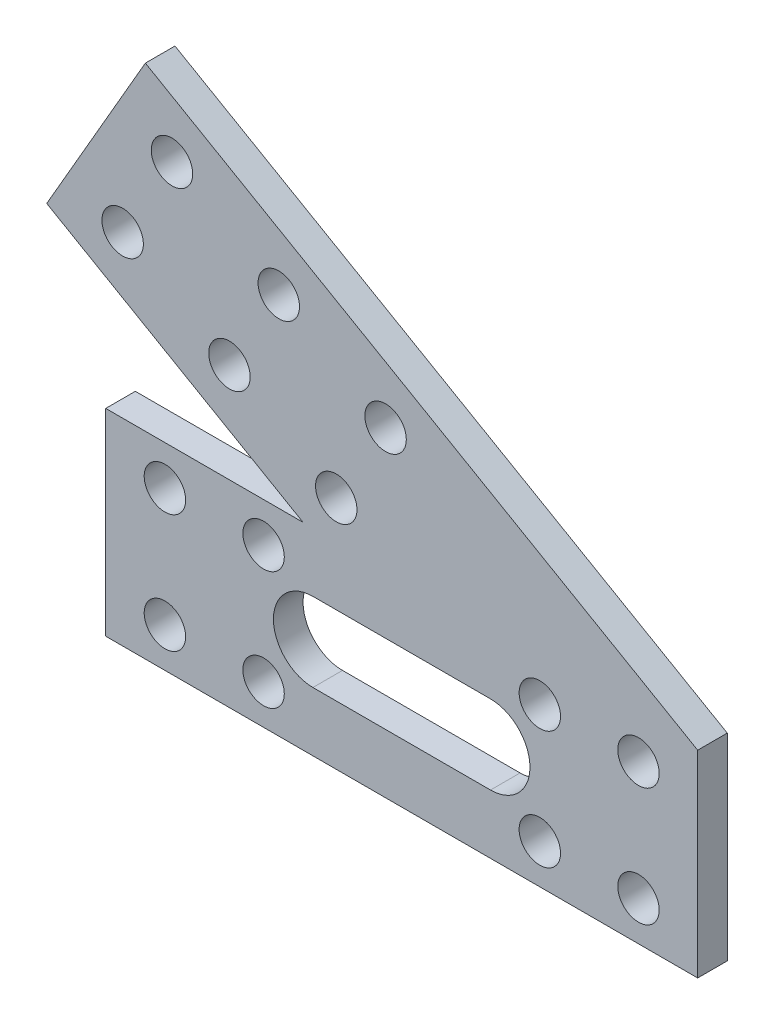
SolidWorks part; units mm, degrees
material "Thornel VCB-20 碳布"
ref_plane "前视基准面" through (0, 0, 0) normal (0, 0, 1) x (1, 0, 0)
ref_plane "上视基准面" through (0, 0, 0) normal (0, 1, 0) x (1, 0, 0)
ref_plane "右视基准面" through (0, 0, 0) normal (1, 0, 0) x (0, 0, -1)
other "Configuration Table"
sketch "草图1" plane through (0, 0, 0) normal (0, 0, 1) x (1, 0, 0)
  line L0 (60, 0) -> (0, 0)
  line L1 (0, 0) -> (0, 20)
  line L2 (0, 20) -> (60, 20) construction
  line L9 (60, 20) -> (60, 0)
  line L11 (20, 20) -> (-5.9808, 35)
  line L12 (-5.9808, 35) -> (4.0192, 52.3205)
  line L13 (4.0192, 52.3205) -> (60, 20)
  line L14 (20, 20) -> (0, 20)
  dimension "D1" = 20
  dimension "D2" = 60
  dimension "D3" = 150
  dimension "D4" = 30
  dimension "D5" = 20
  dimension "D6" = 30
extrude "凸台-拉伸1" add sketch "草图1" along normal blind 3
sketch "草图2" plane through (0, 0, 3) normal (0, 0, 1) x (1, 0, 0)
  line L0 (6.7154, 44.9904) -> (1.7154, 36.3301) construction
  line L1 (1.7154, 36.3301) -> (23.366, 23.8301) construction
  line L2 (23.366, 23.8301) -> (28.366, 32.4904) construction
  line L3 (28.366, 32.4904) -> (6.7154, 44.9904) construction
  line L4 (4.0192, 52.3205) -> (-5.9808, 35) construction
  line L5 (-5.9808, 35) -> (20, 20) construction
  line L6 (60, 20) -> (4.0192, 52.3205) construction
  line L7 (12.5407, 30.0801) -> (17.5407, 38.7404) construction
  line L9 (20, 20) -> (0, 20) construction
  line L10 (6, 16) -> (54, 16) construction
  line L11 (6, 16) -> (6, 4) construction
  line L12 (6, 4) -> (54, 4) construction
  line L13 (54, 16) -> (54, 4) construction
  line L14 (0, 20) -> (0, 0) construction
  line L15 (21, 10) -> (39, 10) construction
  line L16 (21, 14) -> (39, 14)
  line L17 (21, 6) -> (39, 6)
  line L18 (54, 10) -> (39, 10) construction
  line L19 (60, 0) -> (60, 20) construction
  circle A0 centre (6.7154, 44.9904) radius 2.1
  circle A1 centre (1.7154, 36.3301) radius 2.1
  circle A2 centre (17.5407, 38.7404) radius 2.1
  circle A3 centre (12.5407, 30.0801) radius 2.1
  circle A4 centre (23.366, 23.8301) radius 2.1
  circle A5 centre (28.366, 32.4904) radius 2.1
  circle A6 centre (6, 16) radius 2.1
  circle A7 centre (6, 4) radius 2.1
  circle A8 centre (54, 16) radius 2.1
  circle A9 centre (54, 4) radius 2.1
  circle A10 centre (16, 16) radius 2.1
  circle A11 centre (16, 4) radius 2.1
  circle A12 centre (44, 16) radius 2.1
  circle A13 centre (44, 4) radius 2.1
  arc A14 (21, 14) -> (21, 6) centre (21, 10) ccw
  arc A15 (39, 6) -> (39, 14) centre (39, 10) ccw
  point P38 (30, 10)
  dimension "D5" = 4.2
  dimension "D10" = 4.2
  dimension "D17" = 4
  dimension "D1" = 10
  dimension "D2" = 5
  dimension "D3" = 25
  dimension "D4" = 6
  dimension "D6" = 12
  dimension "D7" = 4
  dimension "D8" = 48
  dimension "D9" = 6
  dimension "D11" = 10
  dimension "D12" = 10
  dimension "D13" = 10
  dimension "D14" = 10
  dimension "D15" = 18
  dimension "D16" = 30
extrude "切除-拉伸1" cut sketch "草图2" against normal blind 10
